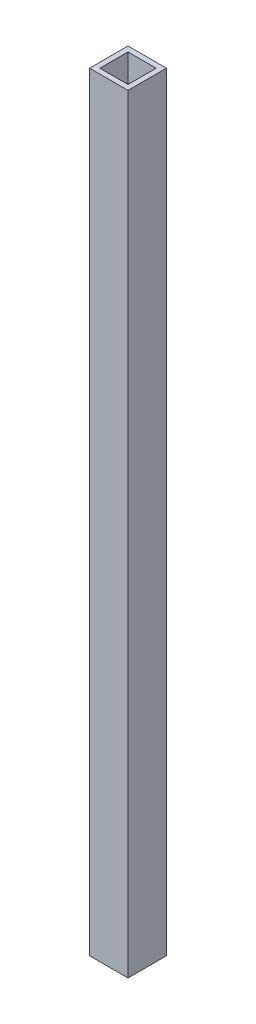
SolidWorks part; units mm, degrees
material "6061 Alloy"
ref_plane "Front Plane" through (0, 0, 0) normal (0, 0, 1) x (1, 0, 0)
ref_plane "Top Plane" through (0, 0, 0) normal (0, 1, 0) x (1, 0, 0)
ref_plane "Right Plane" through (0, 0, 0) normal (1, 0, 0) x (0, 0, -1)
sketch "Sketch1" plane through (0, 0, 0) normal (0, 1, 0) x (1, 0, 0)
  line L0 (2, 2) -> (2, 13)
  line L1 (0, 0) -> (15, 0)
  line L2 (0, 0) -> (0, 15)
  line L3 (0, 15) -> (15, 15)
  line L4 (15, 0) -> (15, 15)
  line L5 (2, 13) -> (13, 13)
  line L6 (13, 2) -> (13, 13)
  line L7 (2, 2) -> (13, 2)
  dimension "D1" = 15
  dimension "D2" = 2
extrude "Boss-Extrude1" add sketch "Sketch1" along normal blind 300
